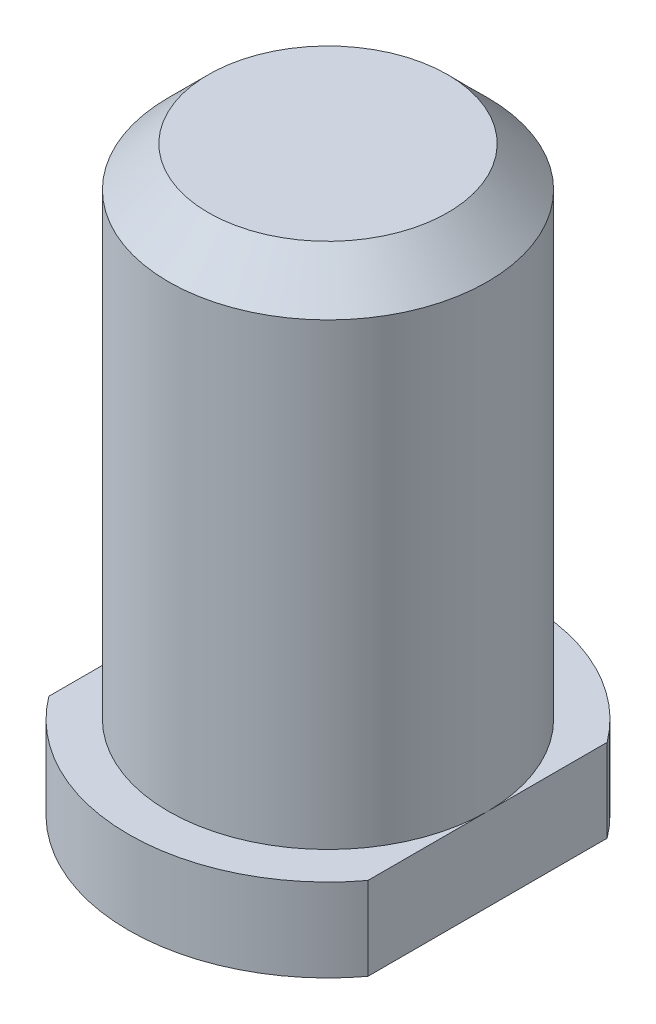
SolidWorks part; units mm, degrees
ref_plane "Front Plane" through (0, 0, 0) normal (0, 0, 1) x (1, 0, 0)
ref_plane "Top Plane" through (0, 0, 0) normal (0, 1, 0) x (1, 0, 0)
ref_plane "Right Plane" through (0, 0, 0) normal (1, 0, 0) x (0, 0, -1)
sketch "Sketch1" plane through (0, 0, 0) normal (0, 1, 0) x (1, 0, 0)
  circle A0 centre (0, 0) radius 3.048
  dimension "D1" = 6.096
extrude "Boss-Extrude1" add sketch "Sketch1" along normal blind 9.525
chamfer "Chamfer1" distance 0.762 angle 45 1 edges at (0, 9.525, 3.048)
sketch "Sketch2" plane through (0, 0, 0) normal (0, -1, 0) x (1, 0, 0)
  circle A0 centre (0, 0) radius 3.81
  dimension "D1" = 7.62
extrude "Boss-Extrude2" add sketch "Sketch2" along normal blind 1.5875
sketch "Sketch4" plane through (0, 0, 0) normal (0, 1, 0) x (1, 0, 0)
  line L1 (-8.2078, -4.6346) -> (-3.048, -4.6346)
  line L2 (-8.2078, -4.6346) -> (-8.2078, 4.6346)
  line L3 (-8.2078, 4.6346) -> (-3.048, 4.6346)
  line L4 (-3.048, -4.6346) -> (-3.048, 4.6346)
  line L5 (-8.2078, -4.6346) -> (-3.048, 4.6346) construction
  line L6 (-8.2078, 4.6346) -> (-3.048, -4.6346) construction
  line L7 (12.6673, -4.2292) -> (3.048, -4.2292)
  line L8 (12.6673, -4.2292) -> (12.6673, 4.2292)
  line L9 (12.6673, 4.2292) -> (3.048, 4.2292)
  line L10 (3.048, -4.2292) -> (3.048, 4.2292)
  line L11 (12.6673, -4.2292) -> (3.048, 4.2292) construction
  line L12 (12.6673, 4.2292) -> (3.048, -4.2292) construction
  circle A0 centre (0, 0) radius 3.048 construction
  circle A1 centre (0, 0) radius 3.048 construction
  point P0 (-5.6279, 0)
  point P5 (7.8577, 0)
extrude "Cut-Extrude1" cut sketch "Sketch4" against normal through all
